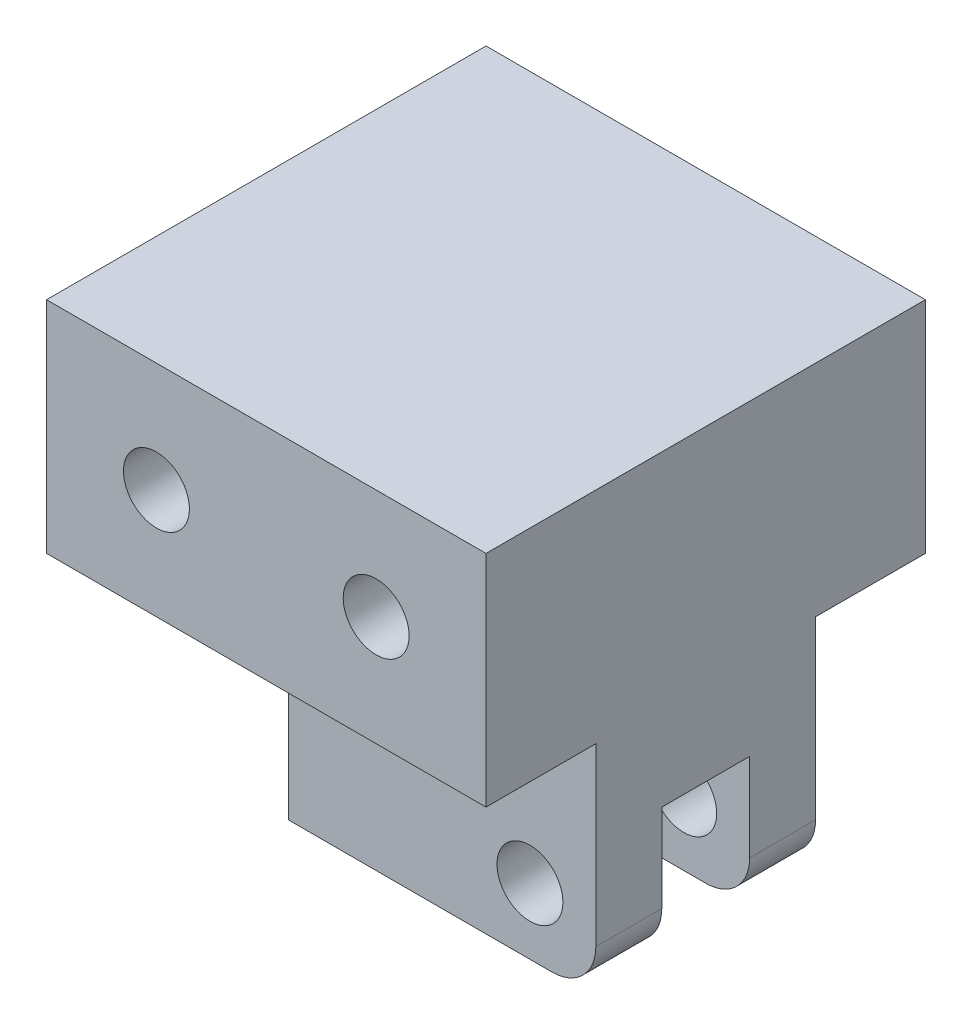
SolidWorks part; units mm, degrees
ref_plane "Front Plane" through (0, 0, 0) normal (0, 0, 1) x (1, 0, 0)
ref_plane "Top Plane" through (0, 0, 0) normal (0, 1, 0) x (1, 0, 0)
ref_plane "Right Plane" through (0, 0, 0) normal (1, 0, 0) x (0, 0, -1)
sketch "Sketch1" plane through (0, 0, 0) normal (1, 0, 0) x (0, 0, -1)
  line L1 (0, 0) -> (-100, 0)
  line L2 (0, 0) -> (0, 50)
  line L3 (0, 50) -> (-100, 50)
  line L4 (-100, 0) -> (-100, 50)
  dimension "D1" = 100
  dimension "D2" = 50
extrude "Boss-Extrude1" add sketch "Sketch1" along normal blind 100
sketch "Sketch2" plane through (0, 0, 0) normal (0, 0, -1) x (-1, 0, 0)
  line L0 (-100, 50) -> (0, 50) construction
  line L1 (0, 0) -> (0, 50) construction
  line L2 (-100, 0) -> (-100, 50) construction
  circle A0 centre (-75, 25) radius 7.5
  circle A1 centre (-25, 25) radius 7.5
  dimension "D1" = 15
  dimension "D2" = 15
  dimension "D3" = 25
  dimension "D4" = 25
  dimension "D5" = 25
  dimension "D6" = 25
extrude "Cut-Extrude1" cut sketch "Sketch2" against normal through all
sketch "Sketch3" plane through (0, 0, 0) normal (0, -1, 0) x (1, 0, 0)
  line L0 (100, 100) -> (100, 0) construction
  line L1 (100, 75) -> (30, 75)
  line L2 (100, 75) -> (100, 25)
  line L3 (100, 25) -> (30, 25)
  line L4 (30, 75) -> (30, 25)
  line L5 (100, 100) -> (0, 100) construction
  line L6 (100, 0) -> (0, 0) construction
  dimension "D1" = 25
  dimension "D2" = 25
  dimension "D3" = 70
extrude "Boss-Extrude2" add sketch "Sketch3" along normal blind 50
sketch "Sketch4" plane through (0, 0, 75) normal (0, 0, 1) x (1, 0, 0)
  line L0 (100, -50) -> (100, 0) construction
  line L1 (100, -50) -> (30, -50) construction
  circle A0 centre (85, -35) radius 7.5
  dimension "D1" = 15
  dimension "D2" = 15
  dimension "D3" = 15
extrude "Cut-Extrude2" cut sketch "Sketch4" against normal through all
sketch "Sketch5" plane through (0, -50, 0) normal (0, -1, 0) x (1, 0, 0)
  line L0 (100, 25) -> (100, 75) construction
  line L1 (100, 60) -> (70, 60)
  line L2 (100, 60) -> (100, 40)
  line L3 (100, 40) -> (70, 40)
  line L4 (70, 60) -> (70, 40)
  line L5 (100, 75) -> (30, 75) construction
  dimension "D1" = 20
  dimension "D2" = 15
  dimension "D3" = 30
extrude "Cut-Extrude3" cut sketch "Sketch5" against normal blind 30
fillet "Fillet1" radius 10 3 edges at (100, -50, 32.5) (100, -50, 67.5) (70, -20, 50)
